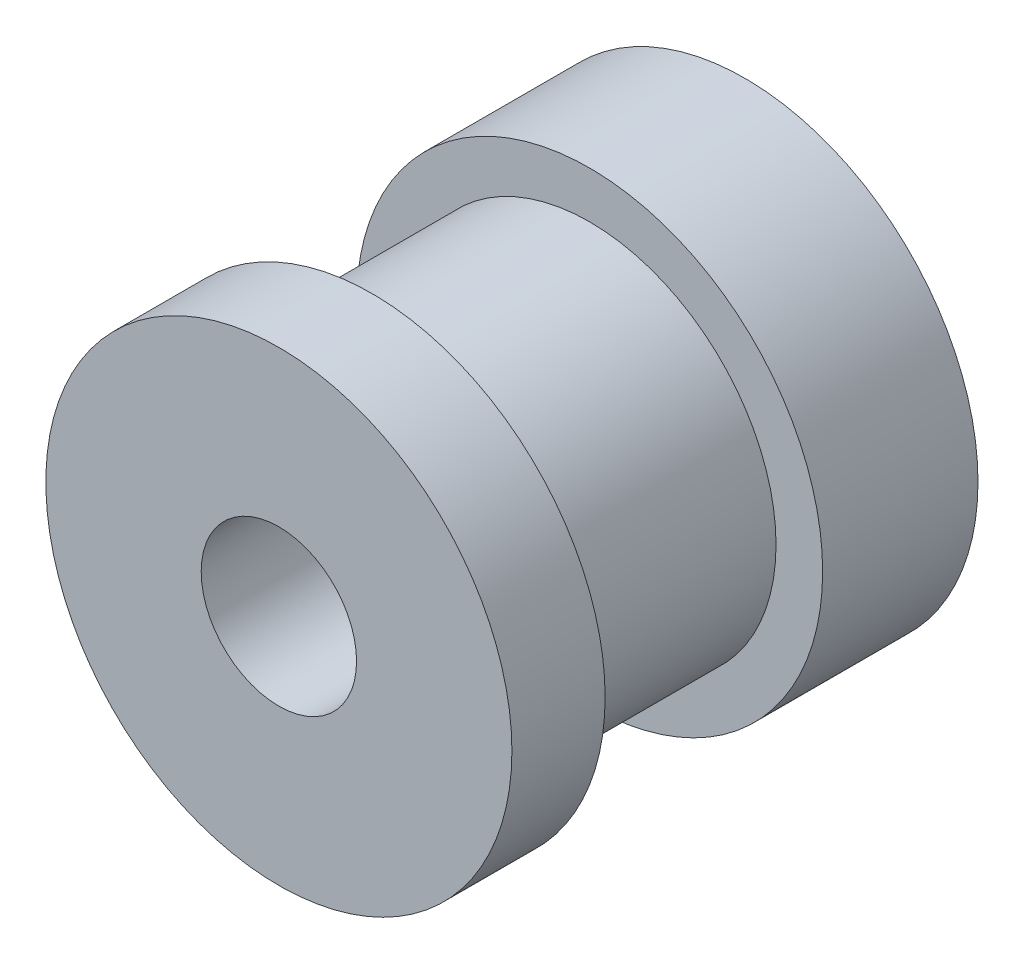
SolidWorks part; units mm, degrees
ref_plane "Plan de face" through (0, 0, 0) normal (0, 0, 1) x (1, 0, 0)
ref_plane "Plan de dessus" through (0, 0, 0) normal (0, 1, 0) x (1, 0, 0)
ref_plane "Plan de droite" through (0, 0, 0) normal (1, 0, 0) x (0, 0, -1)
sketch "Esquisse1" plane through (0, 0, 0) normal (0, 0, 1) x (1, 0, 0)
  circle A0 centre (0, 0) radius 7.5
  dimension "D1" = 15
extrude "Boss.-Extru.1" add sketch "Esquisse1" along normal blind 5
sketch "Esquisse2" plane through (0, 0, 5) normal (0, 0, 1) x (1, 0, 0)
  circle A0 centre (0, 0) radius 6
  dimension "D1" = 12
extrude "Boss.-Extru.2" add sketch "Esquisse2" along normal blind 7
sketch "Esquisse3" plane through (0, 0, 12) normal (0, 0, 1) x (1, 0, 0)
  circle A0 centre (0, 0) radius 7.5
  dimension "D1" = 15
extrude "Boss.-Extru.3" add sketch "Esquisse3" along normal blind 3
sketch "Esquisse4" plane through (0, 0, 0) normal (0, 0, -1) x (-1, 0, 0)
  circle A0 centre (0, 0) radius 2.5
extrude "Enlèv. mat.-Extru.1" cut sketch "Esquisse4" against normal blind 30
